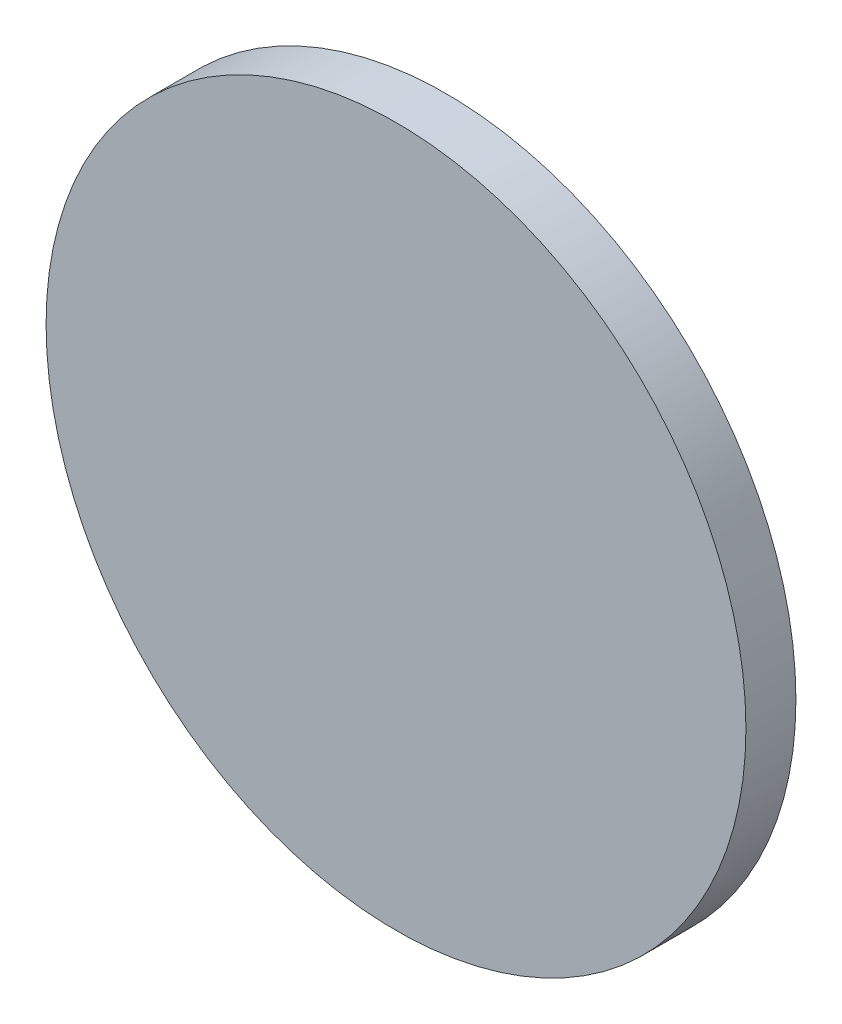
SolidWorks part; units mm, degrees
ref_plane "Alzado" through (0, 0, 0) normal (0, 0, 1) x (1, 0, 0)
ref_plane "Planta" through (0, 0, 0) normal (0, 1, 0) x (1, 0, 0)
ref_plane "Vista lateral" through (0, 0, 0) normal (1, 0, 0) x (0, 0, -1)
sketch "Croquis1" plane through (0, 0, 0) normal (0, 0, 1) x (1, 0, 0)
  circle A0 centre (0, 0) radius 7
  dimension "D1" = 14
extrude "Saliente-Extruir1" add sketch "Croquis1" along normal blind 1
sketch "Croquis2" plane through (0, 0, 1) normal (0, 0, 1) x (1, 0, 0)
  circle A0 centre (0, 0) radius 5
  dimension "D1" = 10
extrude "Cortar-Extruir1" cut sketch "Croquis2" against normal blind 2
sketch3d "Croquis3D1"
  line L0 (0, 0, 0) -> (0, 0, 0.659) construction
  line L1 (0, 0, 0.659) -> (0, -7.2599, 0.659) construction
ref_plane "Plano1" through (0, 0, 0) normal (0, 0, 1) x (1, 0, 0)
sketch "Croquis3" plane through (0, 0, 0) normal (0, 0, 1) x (1, 0, 0)
  circle A0 centre (0, 0) radius 5
sketch "Croquis4" plane through (0, 0, 0) normal (0, 0, 1) x (1, 0, 0)
  circle A0 centre (0, 0) radius 5
extrude "Saliente-Extruir3" add sketch "Croquis4" along normal blind 1
